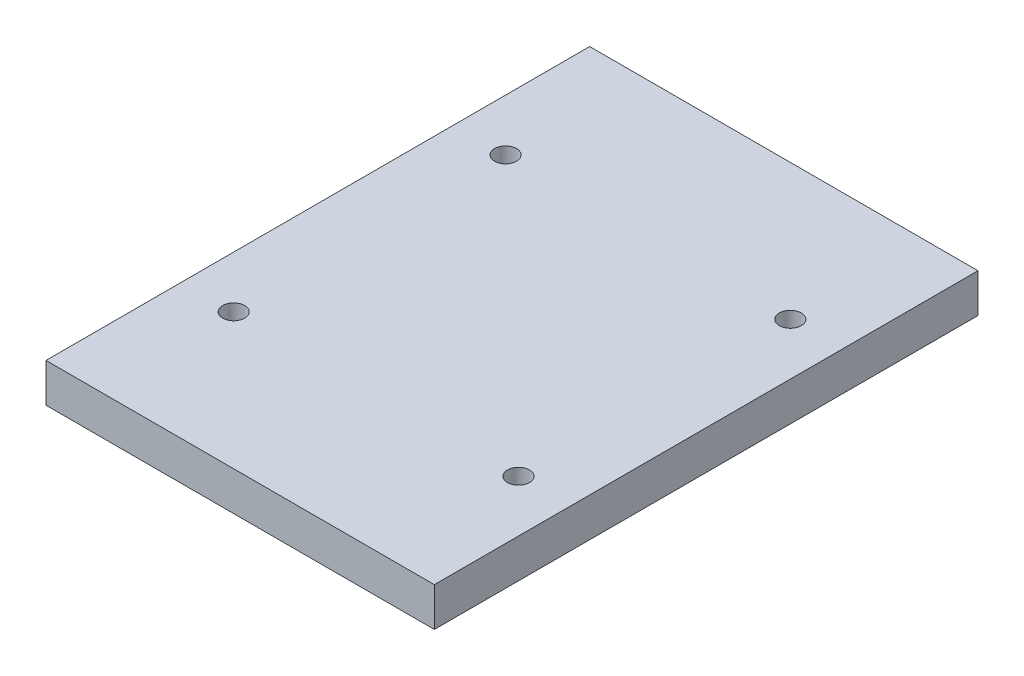
SolidWorks part; units mm, degrees
ref_plane "Front Plane" through (0, 0, 0) normal (0, 0, 1) x (1, 0, 0)
ref_plane "Top Plane" through (0, 0, 0) normal (0, 1, 0) x (1, 0, 0)
ref_plane "Right Plane" through (0, 0, 0) normal (1, 0, 0) x (0, 0, -1)
ref_plane "PZm34_4" through (0, -34.4, 0) normal (0, 1, 0) x (1, 0, 0)
sketch "Sketch1" plane through (0, -34.4, 0) normal (0, 1, 0) x (1, 0, 0)
  line L0 (-30, -112) -> (30, -112)
  line L1 (30, -112) -> (30, -28)
  line L2 (30, -28) -> (-30, -28)
  line L3 (-30, -28) -> (-30, -112)
extrude "Rail Plate" add sketch "Sketch1" along normal blind 6
ref_plane "PY34" through (0, 0, 34) normal (0, 0, 1) x (1, 0, 0)
sketch "Sketch2" plane through (0, 0, 34) normal (0, 0, 1) x (1, 0, 0)
  line L0 (-14.6667, -33.9) -> (14.6667, -33.9)
  line L1 (14.6667, -33.9) -> (19, -40.4)
  line L2 (19, -40.4) -> (-19, -40.4)
  line L3 (-19, -40.4) -> (-14.6667, -33.9)
extrude "Dovetail Rail" add sketch "Sketch2" along normal blind 72
ref_plane "PZm34_9" through (0, -34.9, 0) normal (0, 1, 0) x (1, 0, 0)
sketch "Sketch3" plane through (0, -34.9, 0) normal (0, 1, 0) x (1, 0, 0)
  circle A0 centre (-22, -91) radius 1.7
  circle A1 centre (-22, -49) radius 1.7
  circle A2 centre (22, -91) radius 1.7
  circle A3 centre (22, -49) radius 1.7
extrude "M3 Holes" cut sketch "Sketch3" along normal blind 7
sketch "Sketch4" plane through (0, -34.9, 0) normal (0, 1, 0) x (1, 0, 0)
  circle A0 centre (-22, -91) radius 3
  circle A1 centre (-22, -49) radius 3
  circle A2 centre (22, -91) radius 3
  circle A3 centre (22, -49) radius 3
extrude "Counterbores" cut sketch "Sketch4" along normal blind 4
ref_plane "PZm40_9" through (0, -40.9, 0) normal (0, 1, 0) x (1, 0, 0)
sketch "Sketch5" plane through (0, -40.9, 0) normal (0, 1, 0) x (1, 0, 0)
  circle A0 centre (0, -98) radius 2.25
  circle A1 centre (0, -42) radius 2.25
extrude "Lock Detents" cut sketch "Sketch5" along normal blind 2.5
equation "\"PlateX\" = 60.0"
equation "\"PlateY\" = 84.0"
equation "\"PlateT\" = 6.0"
equation "\"RailW\" = 30.0"
equation "\"RailW2\" = 38.0"
equation "\"RailH\" = 6.0"
equation "\"RailL\" = 72.0"
